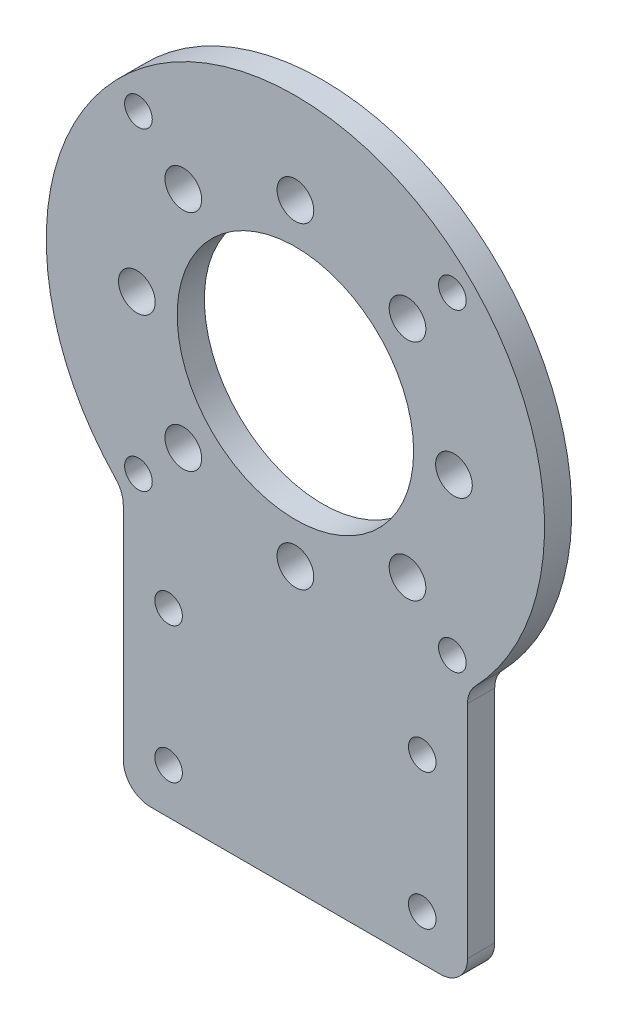
SolidWorks part; units mm, degrees
material "Thornel Mat VMA"
ref_plane "前视基准面" through (0, 0, 0) normal (0, 0, 1) x (1, 0, 0)
ref_plane "上视基准面" through (0, 0, 0) normal (0, 1, 0) x (1, 0, 0)
ref_plane "右视基准面" through (0, 0, 0) normal (1, 0, 0) x (0, 0, -1)
sketch "草图1" plane through (0, 0, 0) normal (0, 0, 1) x (1, 0, 0)
  circle A0 centre (0, 0) radius 21 construction
  circle A1 centre (0, 0) radius 27.5
  circle A2 centre (0, 0) radius 13.05
  dimension "D1" = 42
  dimension "D3" = 26.1
  dimension "D2" = 6.5
extrude "凸台-拉伸1" add sketch "草图1" along normal mid plane 3
sketch "草图2" plane through (0, 0, 1.5) normal (0, 0, 1) x (1, 0, 0)
  circle A0 centre (0, 0) radius 17.5 construction
  circle A1 centre (0, 17.5) radius 2.025
  circle A2 centre (12.3744, 12.3744) radius 2.025
  circle A3 centre (17.5, 0) radius 2.025
  circle A4 centre (12.3744, -12.3744) radius 2.025
  circle A5 centre (0, -17.5) radius 2.025
  circle A6 centre (-12.3744, -12.3744) radius 2.025
  circle A7 centre (-17.5, 0) radius 2.025
  circle A8 centre (-12.3744, 12.3744) radius 2.025
  point P21 (0, 0)
  dimension "D1" = 35
  dimension "D2" = 4.05
  dimension "D3" = 8
extrude "切除-拉伸1" cut sketch "草图2" against normal mid plane 34
sketch "草图4" plane through (0, 0, 1.5) normal (0, 0, 1) x (1, 0, 0)
  line L0 (-19, -19.8809) -> (-19, -48.5)
  line L1 (-19, -48.5) -> (19, -48.5)
  line L2 (19, -48.5) -> (19, -19.8809)
  line L3 (0, 0) -> (0, -48.5) construction
  line L4 (-120.4, -48.5) -> (399.6, -48.5) construction
  circle A0 centre (0, 0) radius 27.5 construction
  circle A2 centre (0, 0) radius 27.5
  arc A3 (-19, -19.8809) -> (19, -19.8809) centre (0, 0) ccw
  dimension "D2" = 38
  dimension "D1" = 0
extrude "凸台-拉伸2" add sketch "草图4" against normal up to surface (3 mm away) up to face at (2.025, 17.5, -1.5)
sketch "草图5" plane through (0, 0, -1.5) normal (0, 0, -1) x (-1, 0, 0)
  line L0 (0, 0) -> (17.3241, 17.3241) construction
  line L1 (0, 24.5) -> (0, 0) construction
  circle A0 centre (0, 0) radius 24.5 construction
  arc A1 (19, -19.8809) -> (-19, -19.8809) centre (0, 0) ccw construction
  circle A2 centre (17.3241, 17.3241) radius 1.525
  circle A3 centre (17.3241, -17.3241) radius 1.525
  circle A4 centre (-17.3241, -17.3241) radius 1.525
  circle A5 centre (-17.3241, 17.3241) radius 1.525
  point P18 (0, 0)
  dimension "D1" = 3
  dimension "D2" = 3.05
  dimension "D3" = 45
  dimension "D4" = 4
extrude "切除-拉伸2" cut sketch "草图5" against normal up to surface (3 mm away) up to face at (2.025, 17.5, 1.5)
sketch "草图6" [suppressed] plane through (0, 0, 1.5) normal (0, 0, 1) x (1, 0, 0)
  circle A0 centre (0, 0) radius 27.5 construction
  circle A1 centre (0, 0) radius 21.5
  dimension "D1" = 55
  dimension "D2" = 6
extrude "切除-拉伸3" [suppressed] cut sketch "草图6" against normal mid plane 30
fillet "圆角1" radius 3 4 edges at (-19, -48.5, 0) (19, -48.5, 0) (19, -19.8809, 0) (-19, -19.8809, 0)
sketch "草图7" plane through (0, 0, -1.5) normal (0, 0, -1) x (-1, 0, 0)
  circle A0 centre (-14, -43.5) radius 1.525 construction
  circle A1 centre (-14, -28.5) radius 1.525 construction
  circle A2 centre (14, -43.5) radius 1.525 construction
  circle A3 centre (14, -28.5) radius 1.525 construction
  circle A4 centre (-14, -43.5) radius 1.525
  circle A5 centre (-14, -28.5) radius 1.525
  circle A6 centre (14, -43.5) radius 1.525
  circle A7 centre (14, -28.5) radius 1.525
extrude "切除-拉伸4" cut sketch "草图7" against normal mid plane 10
